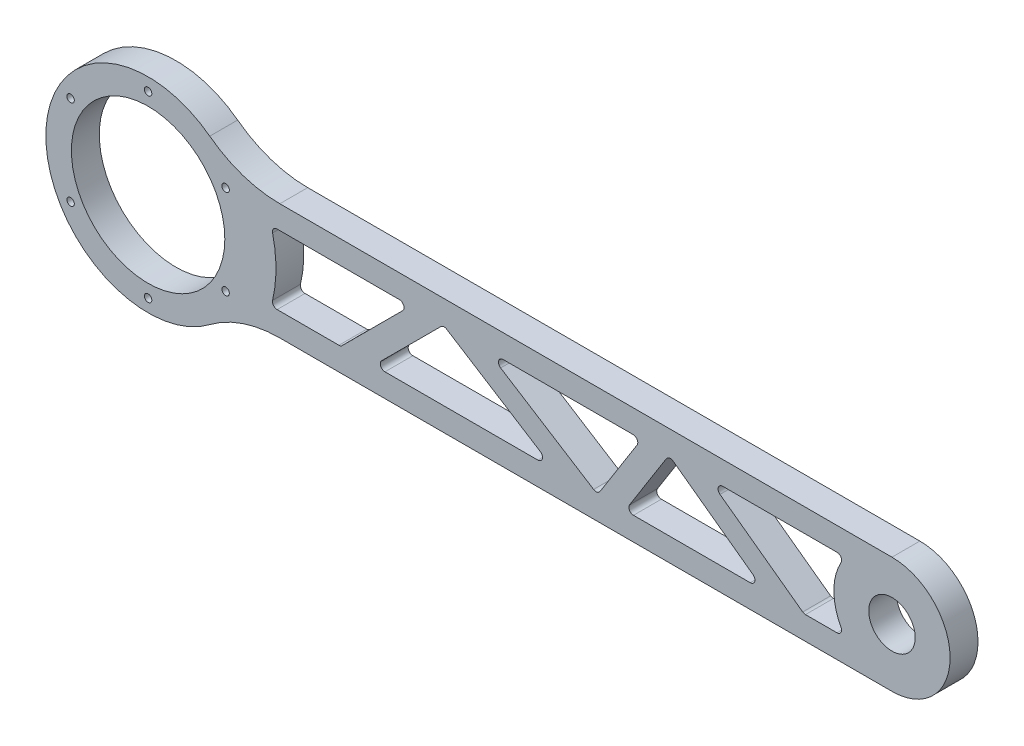
SolidWorks part; units mm, degrees
material "环氧树脂FR-4"
ref_plane "前视基准面" through (0, 0, 0) normal (0, 0, 1) x (1, 0, 0)
ref_plane "上视基准面" through (0, 0, 0) normal (0, 1, 0) x (1, 0, 0)
ref_plane "右视基准面" through (0, 0, 0) normal (1, 0, 0) x (0, 0, -1)
sketch "草图1" plane through (0, 0, 0) normal (0, 0, 1) x (1, 0, 0)
  line L0 (0, 0) -> (320, 0) construction
  line L3 (320, 25) -> (56.6657, 25)
  line L4 (320, -25) -> (56.6657, -25)
  arc A2 (26.5244, 35.1064) -> (26.5244, -35.1064) centre (0, 0) ccw
  arc A3 (320, -25) -> (320, 25) centre (320, 0) ccw
  arc A4 (26.5244, -35.1064) -> (56.6657, -25) centre (56.6657, -75) cw
  arc A5 (26.5244, 35.1064) -> (56.6657, 25) centre (56.6657, 75) ccw
  dimension "D1" = 88
  dimension "D3" = 50
  dimension "D4" = 50
  dimension "D5" = 50
  dimension "D2" = 320
extrude "凸台-拉伸1" add sketch "草图1" along normal blind 12
sketch "草图3" plane through (0, 0, 12) normal (0, 0, 1) x (1, 0, 0)
  circle A0 centre (0, 0) radius 38.5 construction
  point P8 (0, 38.5)
  point P10 (33.342, 19.25)
  point P11 (33.342, -19.25)
  point P12 (0, -38.5)
  point P13 (-33.342, -19.25)
  point P14 (-33.342, 19.25)
  dimension "D1" = 77
  dimension "D2" = 6
sketch "草图5" plane through (0, 0, 12) normal (0, 0, 1) x (1, 0, 0)
  circle A0 centre (0, 0) radius 33
  circle A1 centre (320, 0) radius 10
  dimension "D1" = 66
  dimension "D2" = 20
extrude "切除-拉伸1" cut sketch "草图5" against normal through all
sketch "草图6" plane through (0, 0, 12) normal (0, 0, 1) x (1, 0, 0)
  line L4 (112.915, 15) -> (82.915, -15)
  line L6 (97.0572, -15) -> (174.6043, -15)
  line L7 (174.6043, -15) -> (127.0572, 15)
  line L8 (127.0572, 15) -> (97.0572, -15)
  line L9 (145.7973, 15) -> (212.273, 15)
  line L10 (212.273, 15) -> (193.3444, -15)
  line L11 (193.3444, -15) -> (145.7973, 15)
  line L12 (320, 25) -> (56.6657, 25) construction
  line L17 (72.915, -15) -> (52.915, -15)
  line L18 (56.6657, -25) -> (320, -25) construction
  line L19 (205.1686, -15) -> (224.0971, 15)
  line L20 (224.0971, 15) -> (265.1686, -15)
  line L21 (205.1686, -15) -> (265.1686, -15)
  line L22 (241.0509, 15) -> (282.1223, -15)
  line L23 (282.1223, -15) -> (300, -15)
  line L24 (241.0509, 15) -> (300, 15)
  line L26 (72.915, -15) -> (82.915, -15)
  line L27 (52.915, 15) -> (112.915, 15)
  arc A0 (52.915, -15) -> (52.915, 15) centre (0, 0) ccw
  arc A1 (300, 15) -> (300, -15) centre (320, 0) ccw
  dimension "D2" = 110
  dimension "D3" = 10
  dimension "D4" = 10
  dimension "D5" = 60
  dimension "D6" = 20
  dimension "D7" = 0
  dimension "D8" = 10
  dimension "D9" = 10
  dimension "D11" = 10
  dimension "D12" = 77.5471
  dimension "D13" = 0
  dimension "D14" = 0
  dimension "D15" = 10
  dimension "D16" = 10
  dimension "D17" = 10
  dimension "D18" = 10
  dimension "D19" = 60
  dimension "D20" = 0
  dimension "D21" = 10
  dimension "D22" = 0
extrude "切除-拉伸2" cut sketch "草图6" against normal through all
fillet "圆角1" radius 2 17 edges at (300, 15, 6) (300, -15, 6) (282.1223, -15, 6) (241.0509, 15, 6) (265.1686, -15, 6) (205.1686, -15, 6) (224.0971, 15, 6) (212.273, 15, 6) (145.7973, 15, 6) (193.3444, -15, 6) (174.6043, -15, 6) (97.0572, -15, 6) (127.0572, 15, 6) (112.915, 15, 6) (82.915, -15, 6) (52.915, -15, 6) (52.915, 15, 6)
hole_wizard "Ø3.2 (3.2) 直径孔1" positions "3D草图2" profile "草图8" hole size "Ø3.2" standard "GB" end condition through all
sketch3d "3D草图2"
  point P0 (0, 38.5, 12)
  point P3 (-33.342, 19.25, 12)
  point P6 (-33.342, -19.25, 12)
  point P9 (0, -38.5, 12)
  point P12 (33.342, -19.25, 12)
  point P15 (33.342, 19.25, 12)
sketch "草图8" plane through (0, 38.5, 12) normal (1, 0, 0) x (0, -1, 0)
  line L0 (0, 0) -> (0, 12)
  line L1 (0, 12) -> (1.6, 12)
  line L2 (1.6, 12) -> (1.6, 0)
  line L5 (1.6, 0) -> (0, 0)
  line L11 (0, -6.35) -> (0, 107.95) construction
  dimension "通孔孔直径" = 3.2
  dimension "通孔孔深度" = 12
